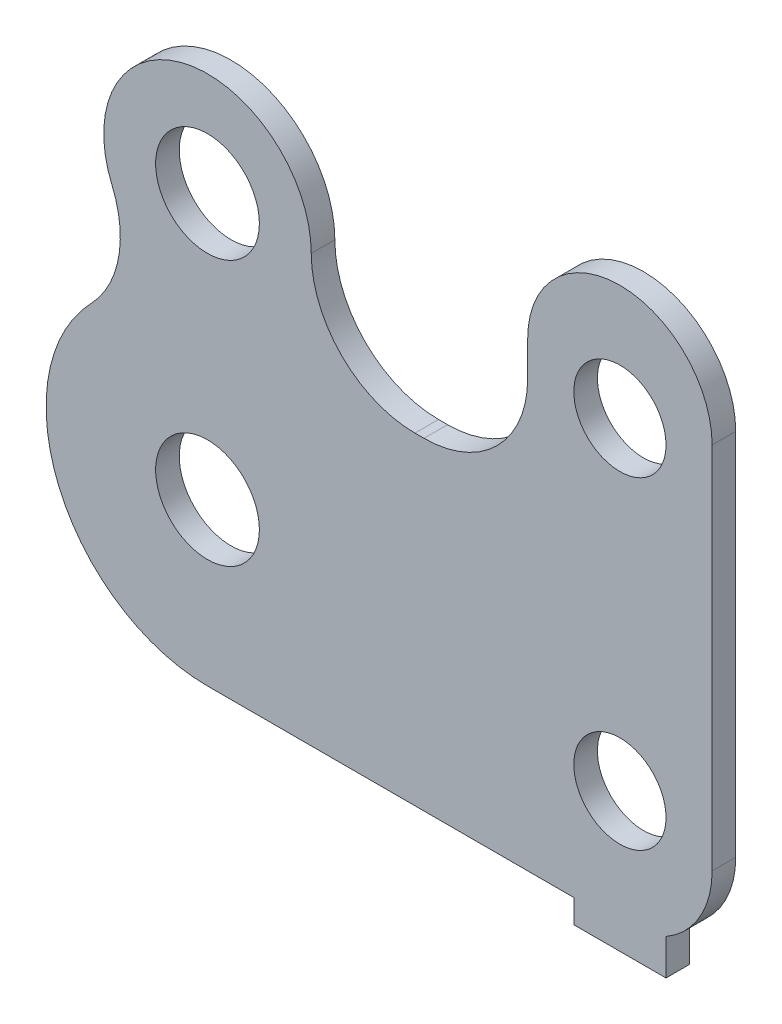
SolidWorks part; units mm, degrees
ref_plane "Front Plane" through (0, 0, 0) normal (0, 0, 1) x (1, 0, 0)
ref_plane "Top Plane" through (0, 0, 0) normal (0, 1, 0) x (1, 0, 0)
ref_plane "Right Plane" through (0, 0, 0) normal (1, 0, 0) x (0, 0, -1)
sketch "Sketch1" plane through (0, 0, 0) normal (0, 0, 1) x (1, 0, 0)
  line L2 (0, 5.5562) -> (0, -5.5562) construction
  line L6 (0, 5.5562) -> (0, -12.7) construction
  line L9 (17.374, 13.4938) -> (11.024, 13.4938)
  line L10 (11.024, 13.4938) -> (11.024, 5.5563)
  line L11 (17.374, 13.4938) -> (17.374, -5.5562)
  line L12 (17.374, -5.5562) -> (0, -5.5562)
  line L13 (11.024, 5.5563) -> (11.024, -5.5563) construction
  line L14 (14.199, 13.4938) -> (14.199, -5.5563) construction
  line L15 (14.199, 9.525) -> (14.199, -1.5875)
  line L16 (0, 5.5562) -> (11.024, 5.5563)
  line L17 (15.7865, -5.5562) -> (15.7865, -5.1309)
  line L18 (12.6115, -5.5563) -> (15.7865, -5.5562)
  line L19 (12.6115, -5.5563) -> (12.6115, -6.3691)
  line L20 (12.6115, -6.3691) -> (15.7865, -6.369)
  line L21 (15.7865, -5.5562) -> (15.7865, -6.369)
  circle A0 centre (0, 0) radius 5.5562 construction
  arc A2 (0, 5.5562) -> (0, -5.5562) centre (0, 0) ccw
  circle A4 centre (0, 0) radius 1.7859
  circle A10 centre (0, 9.1281) radius 3.5719
  circle A15 centre (0, 9.1281) radius 1.7859
  circle A16 centre (14.199, 9.525) radius 1.5875
  circle A20 centre (14.199, -1.5875) radius 1.5875
  circle A21 centre (7.4522, 9.1281) radius 3.5719
  circle A22 centre (0, 0) radius 12.7 construction
  circle A25 centre (0, 0) radius 9.1281 construction
  circle A26 centre (-6.5741, 6.3327) radius 3.5719
  circle A29 centre (14.199, 10.3188) radius 3.175
  circle A30 centre (14.199, -2.3813) radius 3.175
  circle A31 centre (7.1437, 9.1281) radius 3.5719
  point P17 (14.199, -5.5563)
  point P20 (14.199, 3.9688)
  dimension "D1" = 11.1125
  dimension "D2" = 11.1125
  dimension "D3" = 3.5719
  dimension "D5" = 6.35
  dimension "D6" = 7.1437
  dimension "D7" = 3.5719
  dimension "D8" = 3.175
  dimension "D9" = 0.8128
  dimension "D4" = 19.05
  dimension "D10" = 3.175
extrude "Boss-Extrude1" add sketch "Sketch1" along normal blind 0.8128
